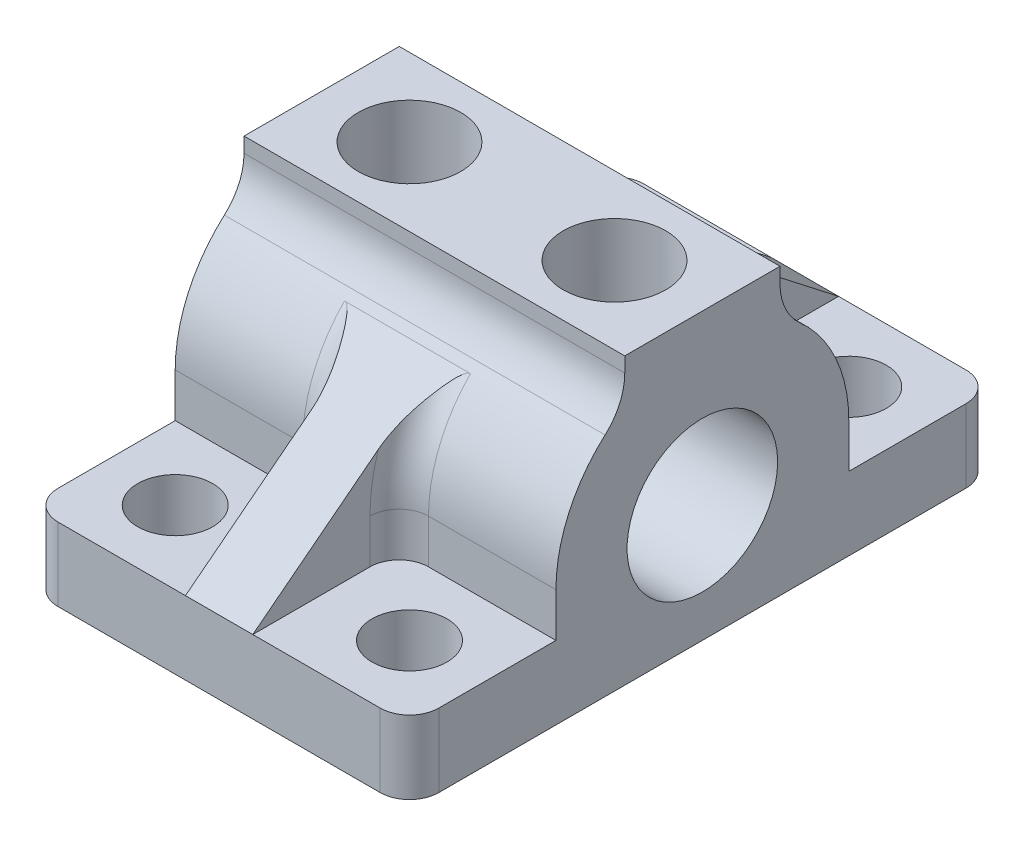
SolidWorks part; units mm, degrees
material "PLA2"
ref_plane "Front Plane" through (0, 0, 0) normal (0, 0, 1) x (1, 0, 0)
ref_plane "Top Plane" through (0, 0, 0) normal (0, 1, 0) x (1, 0, 0)
ref_plane "Right Plane" through (0, 0, 0) normal (1, 0, 0) x (0, 0, -1)
sketch "Sketch1" plane through (0, 0, 0) normal (1, 0, 0) x (0, 0, -1)
  line L0 (0, 0) -> (27506.0917, 0) construction
  line L1 (0.3138, 24.13) -> (27506.4055, 24.13) construction
  line L2 (0, 29.21) -> (0, 0) construction
  line L3 (12.7, 24.13) -> (-12.7, 24.13)
  line L4 (-12.7, 24.13) -> (-12.7, 27.305)
  line L5 (-12.7, 27.305) -> (-6.35, 27.305)
  line L6 (-6.35, 27.305) -> (-6.35, 29.21)
  line L7 (0, 29.21) -> (0, 35.56) construction
  line L8 (6.35, 27.305) -> (6.35, 29.21)
  line L9 (12.7, 27.305) -> (6.35, 27.305)
  line L10 (12.7, 24.13) -> (12.7, 27.305)
  circle A0 centre (0, 29.21) radius 3.2639
  arc A1 (6.35, 29.21) -> (-6.35, 29.21) centre (0, 29.21) ccw
  point P19 (0, 24.13)
  dimension "D2" = 6.5278
  dimension "D4" = 12.7
  dimension "D7" = 3.0861
  dimension "D1" = 24.13
  dimension "D3" = 29.21
  dimension "D5" = 3.175
  dimension "D6" = 6.35
extrude "Boss-Extrude1" add sketch "Sketch1" along normal mid plane 16.51
sketch "Sketch2" plane through (0, 0, 0) normal (1, 0, 0) x (0, 0, -1)
  line L0 (0, 32.4739) -> (0, 25.9461) construction
  line L1 (-4.5348, 33.655) -> (-12.7, 27.305)
  line L2 (-6.35, 27.305) -> (-12.7, 27.305) construction
  line L3 (-12.7, 27.305) -> (-4.5348, 27.305)
  line L4 (-4.5348, 27.305) -> (-4.5348, 33.655)
  line L5 (4.5348, 27.305) -> (4.5348, 33.655)
  line L6 (12.7, 27.305) -> (4.5348, 27.305)
  line L7 (4.5348, 33.655) -> (12.7, 27.305)
  circle A0 centre (0, 29.21) radius 3.2639 construction
  arc A1 (6.35, 29.21) -> (-6.35, 29.21) centre (0, 29.21) ccw construction
  dimension "D1" = 6.35
extrude "Boss-Extrude2" add sketch "Sketch2" along normal mid plane 2.921
sketch "Sketch3" plane through (0, 27.305, 0) normal (0, 1, 0) x (1, 0, 0)
  line L0 (-8.255, 0) -> (8.255, 0) construction
  line L1 (-8.255, 6.35) -> (-8.255, -6.35) construction
  line L2 (8.255, -6.35) -> (8.255, 6.35) construction
  line L3 (0, 12.7) -> (0, -12.7) construction
  line L4 (1.4605, 12.7) -> (-1.4605, 12.7) construction
  line L5 (1.4605, -12.7) -> (-1.4605, -12.7) construction
  circle A0 centre (-5.08, 9.525) radius 1.6256
  circle A1 centre (5.08, 9.525) radius 1.6256
  circle A2 centre (5.08, -9.525) radius 1.6256
  circle A3 centre (-5.08, -9.525) radius 1.6256
  dimension "D1" = 3.2512
  dimension "D2" = 10.16
  dimension "D3" = 19.05
extrude "Cut-Extrude1" cut sketch "Sketch3" against normal through all
sketch "Sketch4" plane through (8.255, 0, 0) normal (1, 0, 0) x (0, 0, -1)
  line L0 (3.3655, 34.5948) -> (-3.3655, 34.5948)
  arc A0 (6.35, 29.21) -> (-6.35, 29.21) centre (0, 29.21) ccw construction
  arc A1 (3.3655, 34.5948) -> (-3.3655, 34.5948) centre (0, 29.21) ccw
  dimension "D1" = 6.731
extrude "Cut-Extrude2" cut sketch "Sketch4" against normal through all
sketch "Sketch6" plane through (0, 34.5948, 0) normal (0, 1, 0) x (1, 0, 0)
  line L4 (8.255, -3.3655) -> (8.255, 3.3655)
  line L5 (8.255, 3.3655) -> (-8.255, 3.3655)
  line L6 (-8.255, 3.3655) -> (-8.255, -3.3655)
  line L7 (-8.255, -3.3655) -> (8.255, -3.3655)
  line L8 (8.255, -3.3655) -> (8.255, 3.3655)
  line L9 (8.255, 3.3655) -> (-8.255, 3.3655)
  line L10 (-8.255, 3.3655) -> (-8.255, -3.3655)
  line L11 (-8.255, -3.3655) -> (8.255, -3.3655)
  dimension "D1" = 0
extrude "Boss-Extrude3" add sketch "Sketch6" along normal blind 1.905
sketch "Sketch5" plane through (0, 36.4998, 0) normal (0, 1, 0) x (1, 0, 0)
  line L0 (0, 12.7) -> (0, -12.7) construction
  line L1 (1.4605, 12.7) -> (-1.4605, 12.7) construction
  line L2 (1.4605, -12.7) -> (-1.4605, -12.7) construction
  line L3 (-8.255, 0) -> (8.255, 0) construction
  line L6 (-8.255, 3.3655) -> (-8.255, -3.3655) construction
  line L7 (8.255, -3.3655) -> (8.255, 3.3655) construction
  circle A0 centre (-4.445, 0) radius 2.2225
  circle A1 centre (4.445, 0) radius 2.2225
  dimension "D1" = 4.445
  dimension "D2" = 8.89
extrude "Cut-Extrude3" cut sketch "Sketch5" against normal blind 6.35
fillet "Fillet1" radius 1.27 12 edges at (-1.4605, 31.6107, 5.8787) (1.4605, 31.6107, 5.8787) (-1.4605, 31.6107, -5.8787) (1.4605, 31.6107, -5.8787) (-1.4605, 28.2575, 6.35) (1.4605, 28.2575, 6.35) (-1.4605, 28.2575, -6.35) (1.4605, 28.2575, -6.35) (-8.255, 25.7175, -12.7) (8.255, 25.7175, -12.7) (-8.255, 25.7175, 12.7) (8.255, 25.7175, 12.7)
fillet "Fillet2" radius 2.54 2 edges at (0, 34.5948, -3.3655) (0, 34.5948, 3.3655)
